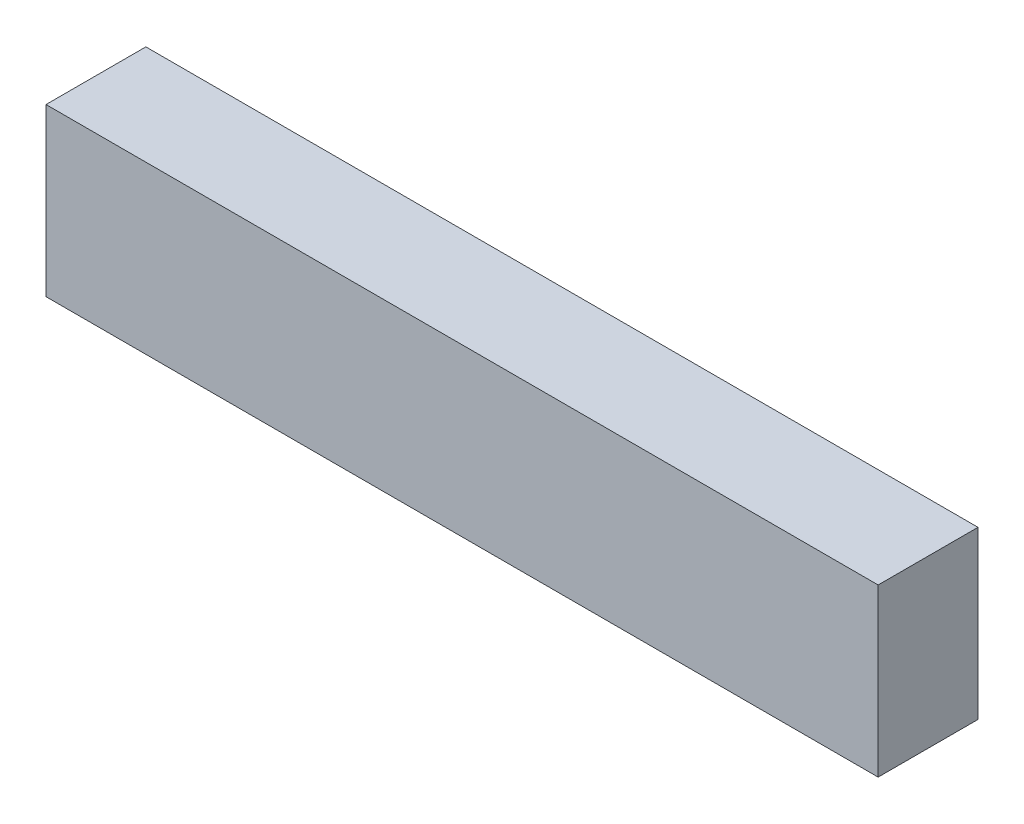
SolidWorks part; units mm, degrees
ref_plane "Plan de face" through (0, 0, 0) normal (0, 0, 1) x (1, 0, 0)
ref_plane "Plan de dessus" through (0, 0, 0) normal (0, 1, 0) x (1, 0, 0)
ref_plane "Plan de droite" through (0, 0, 0) normal (1, 0, 0) x (0, 0, -1)
sketch "Esquisse1" plane through (0, 0, 0) normal (0, 0, 1) x (1, 0, 0)
  line L1 (0, 0) -> (-50, 0)
  line L2 (0, 0) -> (0, 10)
  line L3 (0, 10) -> (-50, 10)
  line L4 (-50, 0) -> (-50, 10)
  dimension "D1" = 10
  dimension "D2" = 50
extrude "Boss.-Extru.1" add sketch "Esquisse1" along normal blind 6
